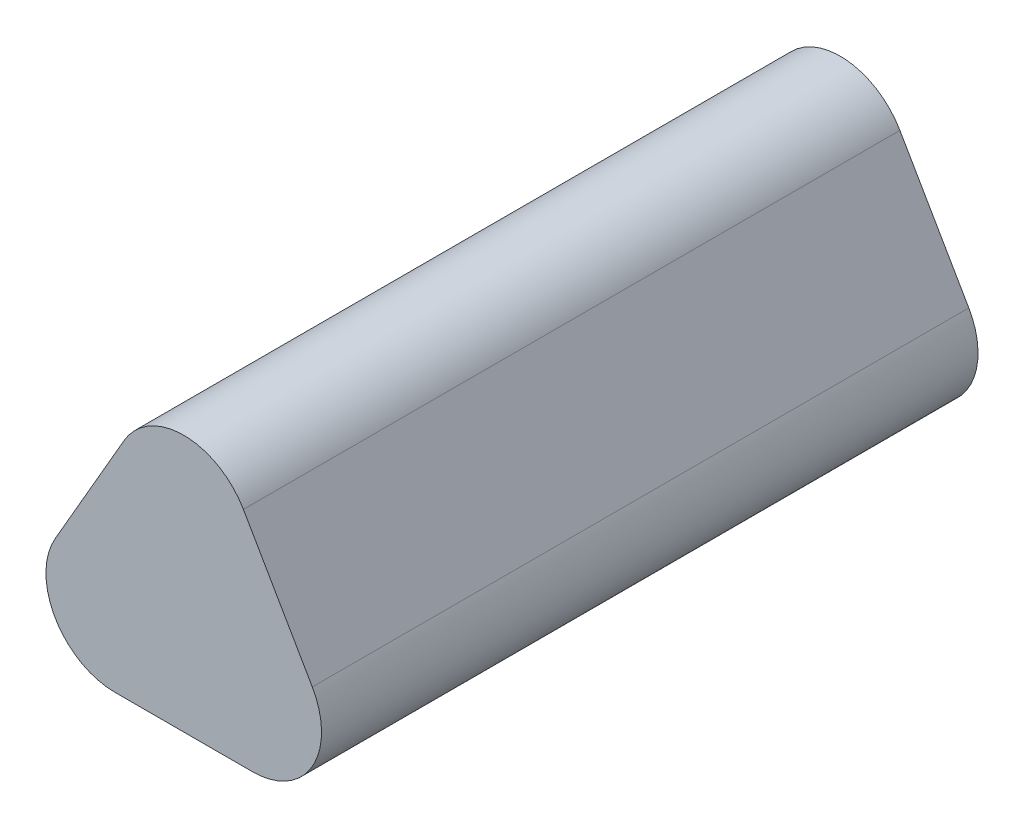
SolidWorks part; units mm, degrees
ref_plane "前视基准面" through (0, 0, 0) normal (0, 0, 1) x (1, 0, 0)
ref_plane "上视基准面" through (0, 0, 0) normal (0, 1, 0) x (1, 0, 0)
ref_plane "右视基准面" through (0, 0, 0) normal (1, 0, 0) x (0, 0, -1)
other "Configuration Table"
sketch "草图1" plane through (0, 0, 0) normal (0, 0, 1) x (1, 0, 0)
  line L0 (-6.8156, 3.935) -> (-14.6856, -9.6962)
  line L1 (-7.87, -21.5012) -> (7.87, -21.5012)
  line L2 (6.8156, 3.935) -> (14.6856, -9.6962)
  arc A0 (6.8156, 3.935) -> (-6.8156, 3.935) centre (0, 0) ccw
  arc A1 (7.87, -21.5012) -> (14.6856, -9.6962) centre (7.87, -13.6312) ccw
  arc A2 (-14.6856, -9.6962) -> (-7.87, -21.5012) centre (-7.87, -13.6312) ccw
  dimension "D1" = 15.74
  dimension "D2" = 15.74
  dimension "D3" = 15.74
extrude "凸台-拉伸1" add sketch "草图1" along normal blind 75
ref_plane "基准面1" through (0, 0, 37.5) normal (0, 0, 1) x (1, 0, 0)
